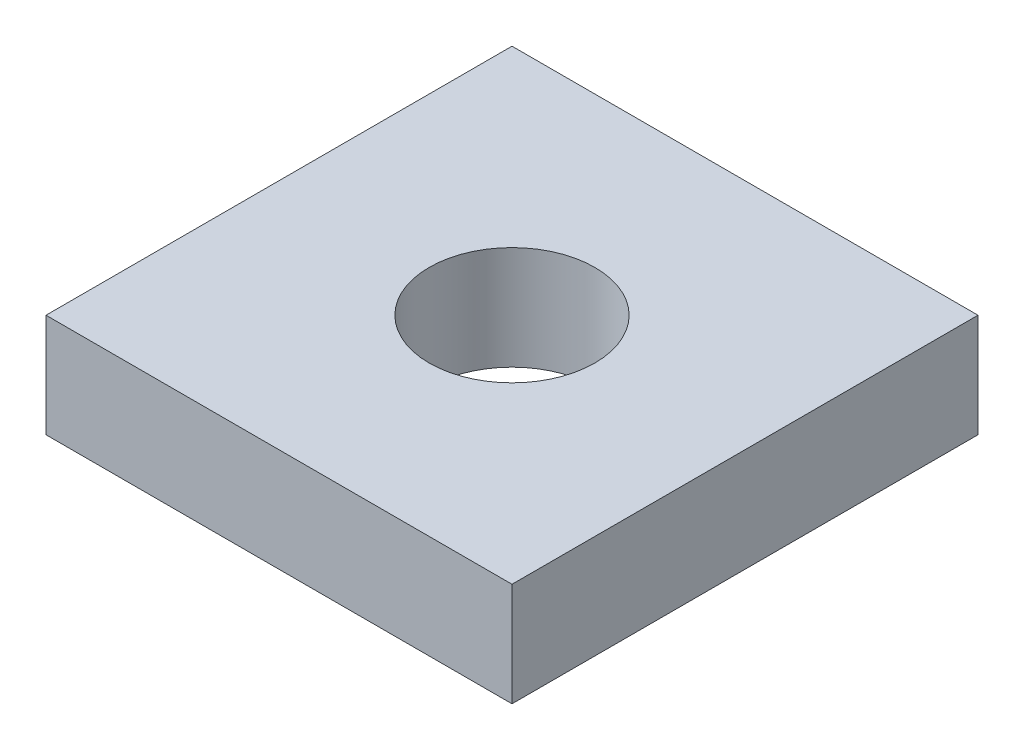
SolidWorks part; units mm, degrees
ref_plane "Ön Düzlem" through (0, 0, 0) normal (0, 0, 1) x (1, 0, 0)
ref_plane "Üst Düzlem" through (0, 0, 0) normal (0, 1, 0) x (1, 0, 0)
ref_plane "Sağ Düzlem" through (0, 0, 0) normal (1, 0, 0) x (0, 0, -1)
sketch "Sketch1" plane through (0, 0, 0) normal (0, 1, 0) x (1, 0, 0)
  line L1 (0, 0) -> (45, 0)
  line L2 (0, 0) -> (0, 45)
  line L3 (0, 45) -> (45, 45)
  line L4 (45, 0) -> (45, 45)
  circle A0 centre (22.5, 22.5) radius 8
  dimension "D1" = 45
  dimension "D2" = 45
extrude "Boss-Extrude1" add sketch "Sketch1" along normal blind 10
